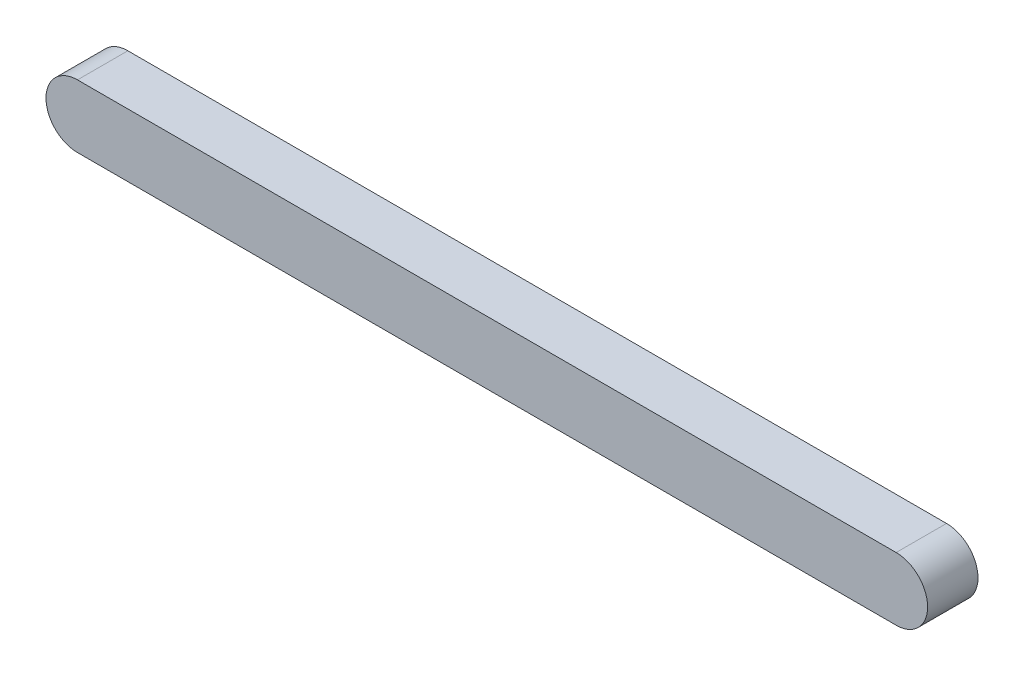
SolidWorks part; units mm, degrees
material "Custom Plastic"
ref_plane "Front Plane" through (0, 0, 0) normal (0, 0, 1) x (1, 0, 0)
ref_plane "Top Plane" through (0, 0, 0) normal (0, 1, 0) x (1, 0, 0)
ref_plane "Right Plane" through (0, 0, 0) normal (1, 0, 0) x (0, 0, -1)
sketch "Sketch1" plane through (0, 0, 0) normal (0, 0, 1) x (1, 0, 0)
  line L1 (-110.433, 15.8144) -> (149.567, 15.8144)
  line L3 (-110.433, -4.1856) -> (149.567, -4.1856)
  arc A0 (-110.433, 15.8144) -> (-110.433, -4.1856) centre (-110.433, 5.8144) ccw
  arc A1 (149.567, 15.8144) -> (149.567, -4.1856) centre (149.567, 5.8144) cw
  dimension "D1" = 260
  dimension "D2" = 20
extrude "Boss-Extrude1" add sketch "Sketch1" along normal blind 16
